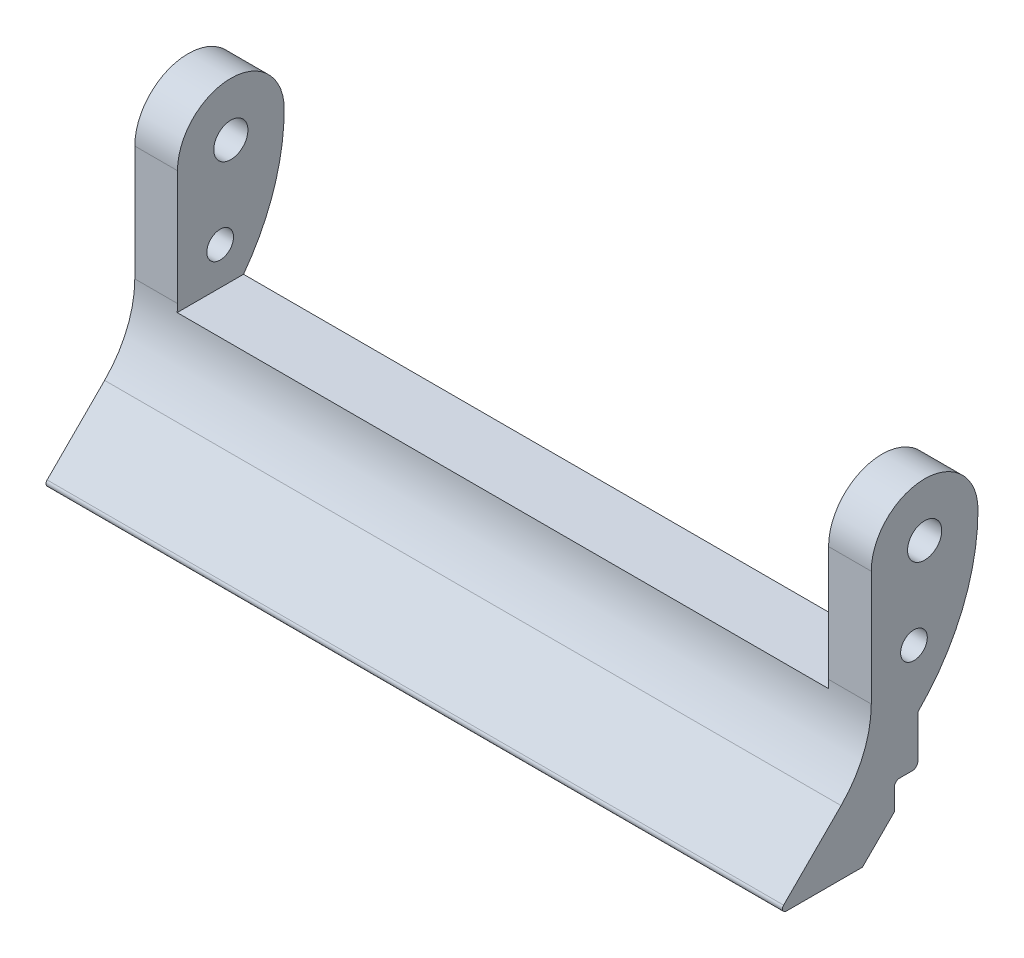
SolidWorks part; units mm, degrees
material "6063-T5"
ref_plane "Front Plane" through (0, 0, 0) normal (0, 0, 1) x (1, 0, 0)
ref_plane "Top Plane" through (0, 0, 0) normal (0, 1, 0) x (1, 0, 0)
ref_plane "Right Plane" through (0, 0, 0) normal (1, 0, 0) x (0, 0, -1)
sketch "Sketch1" plane through (0, 0, 0) normal (1, 0, 0) x (0, 0, -1)
  line L0 (-5, 23.6) -> (-5, 12.8236)
  line L1 (-13.2119, 0.6146) -> (-7.8264, 6)
  line L2 (-12.9573, 0) -> (-5.8264, 0)
  line L3 (55, 0) -> (-55, 0) construction
  line L4 (-5.8264, 0) -> (-2.8409, 2.9855)
  line L6 (-2.8409, 7.7839) -> (-0.6393, 9.9855) construction
  line L9 (-2.8409, 2.9855) -> (-2.8409, 4.9855)
  line L11 (-2.3409, 5.4855) -> (-1.1393, 5.4855)
  line L12 (-0.6393, 5.9855) -> (-0.6393, 9.9855)
  circle A0 centre (0, 23.6) radius 1.6
  arc A1 (-5, 23.6) -> (5, 23.6) centre (0, 23.6) cw
  arc A2 (-7.8264, 6) -> (-5, 12.8236) centre (-14.65, 12.8236) ccw
  arc A3 (-13.2119, 0.6146) -> (-12.9573, 0) centre (-12.9573, 0.36) ccw
  arc A4 (-0.6393, 9.9855) -> (5, 23.6) centre (-14.2538, 23.6) ccw
  arc A5 (-2.8409, 4.9855) -> (-2.3409, 5.4855) centre (-2.3409, 4.9855) cw
  arc A6 (-1.1393, 5.4855) -> (-0.6393, 5.9855) centre (-1.1393, 5.9855) ccw
  point P24 (-2.8409, 5.4855)
  dimension "D1" = 3.2
  dimension "D3" = 9.65
  dimension "D6" = 0.36
  dimension "D11" = 0.5
  dimension "D13" = 0.5
  dimension "D2" = 135
  dimension "D4" = 10
  dimension "D5" = 23.6
  dimension "D7" = 7.6162
  dimension "D8" = 7.1309
  dimension "D10" = 2.9855
  dimension "D12" = 2.5
  dimension "D9" = 4
extrude "Boss-Extrude1" add sketch "Sketch1" along normal blind 69
ref_plane "Plane1" through (4, 0, 0) normal (1, 0, 0) x (0, 0, -1)
sketch "Sketch2" plane through (4, 0, 0) normal (1, 0, 0) x (0, 0, -1)
  line L0 (5, 12.1) -> (-16.169, 12.1)
  line L1 (5, 12.1) -> (5, 28.6)
  line L2 (5, 28.6) -> (-16.169, 28.6)
  line L3 (-16.169, 12.1) -> (-16.169, 28.6)
  arc A0 (5, 23.6) -> (-5, 23.6) centre (0, 23.6) ccw construction
  point P9 (0, 28.6)
  dimension "D1" = 16.5
extrude "Cut-Extrude1" cut sketch "Sketch2" along normal blind 61
hole_wizard "Tap Drill for M3 Tap1" positions "Sketch3" profile "Sketch4" hole size "M3" standard "ISO" end condition through all
sketch "Sketch3" plane through (69, 0, 0) normal (1, 0, 0) x (0, 0, -1)
  circle A0 centre (0, 23.6) radius 1.6 construction
  point P0 (-1, 15.6)
  dimension "D1" = 1
  dimension "D2" = 8
sketch "Sketch4" plane through (69, 15.6, 1) normal (0, 1, 0) x (0, 0, -1)
  line L0 (0, 0) -> (0, 69)
  line L1 (0, 69) -> (1.25, 69)
  line L2 (1.25, 69) -> (1.25, 0)
  line L5 (1.25, 0) -> (0, 0)
  line L11 (0, -6.35) -> (0, 107.95) construction
  dimension "Thru Hole Dia." = 2.5
  dimension "Thru Hole Depth" = 69
cosmetic thread "Cosmetic Thread1" parameters "D1"=5, "D2"=3
cosmetic thread "Cosmetic Thread2" parameters "D1"=5, "D2"=3
equation "\"D5@Sketch1\"=21.6+2"
